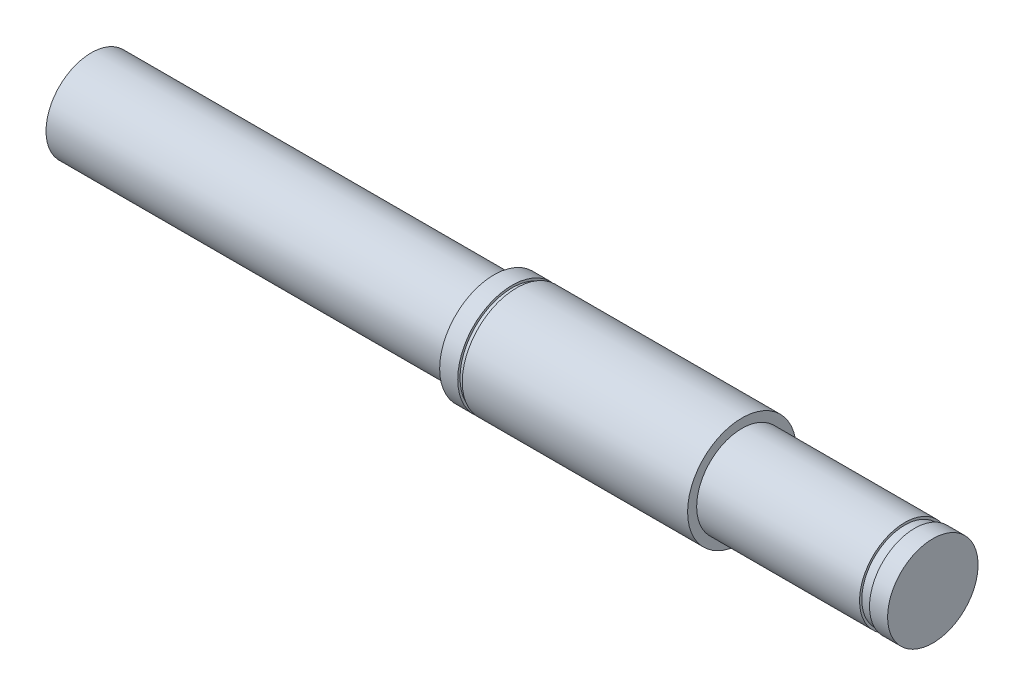
SolidWorks part; units mm, degrees
ref_plane "Front Plane" through (0, 0, 0) normal (0, 0, 1) x (1, 0, 0)
ref_plane "Top Plane" through (0, 0, 0) normal (0, 1, 0) x (1, 0, 0)
ref_plane "Right Plane" through (0, 0, 0) normal (1, 0, 0) x (0, 0, -1)
sketch "Sketch7" plane through (0, 0, 0) normal (0, 0, 1) x (1, 0, 0)
  line L0 (0, 0) -> (1600.6156, 0) construction
  line L1 (-2, 5) -> (-2, 6)
  line L2 (0, 6) -> (-2, 6)
  line L3 (0, 6) -> (0, 5.7496)
  line L4 (-2, 5) -> (-46.5, 5)
  line L5 (-46.5, 5) -> (-46.5, 0)
  line L6 (0, 5.7496) -> (0.5, 5.7496)
  line L7 (0.5, 5.7496) -> (0.5, 6)
  line L8 (0.5, 6) -> (25.4, 6)
  line L9 (25.4, 6) -> (25.4, 5)
  line L10 (25.4, 5) -> (43.4, 5)
  line L11 (43.4, 5) -> (43.4, 4.75)
  line L12 (43.4, 4.75) -> (44.5, 4.75)
  line L13 (44.5, 4.75) -> (44.5, 5)
  line L14 (44.5, 5) -> (46.5, 5)
  line L15 (46.5, 5) -> (46.5, 0)
  line L16 (-46.5, 0) -> (46.5, 0)
  dimension "D1" = 1
  dimension "D2" = 2
  dimension "D3" = 44.5
  dimension "D4" = 5
  dimension "D5" = 0.5
  dimension "D6" = 24.9
  dimension "D7" = 18
  dimension "D8" = 0.25
  dimension "D9" = 0.25
  dimension "D10" = 1.1
  dimension "D11" = 2
revolve "Revolve1" add sketch "Sketch7" angle 360 about L0
